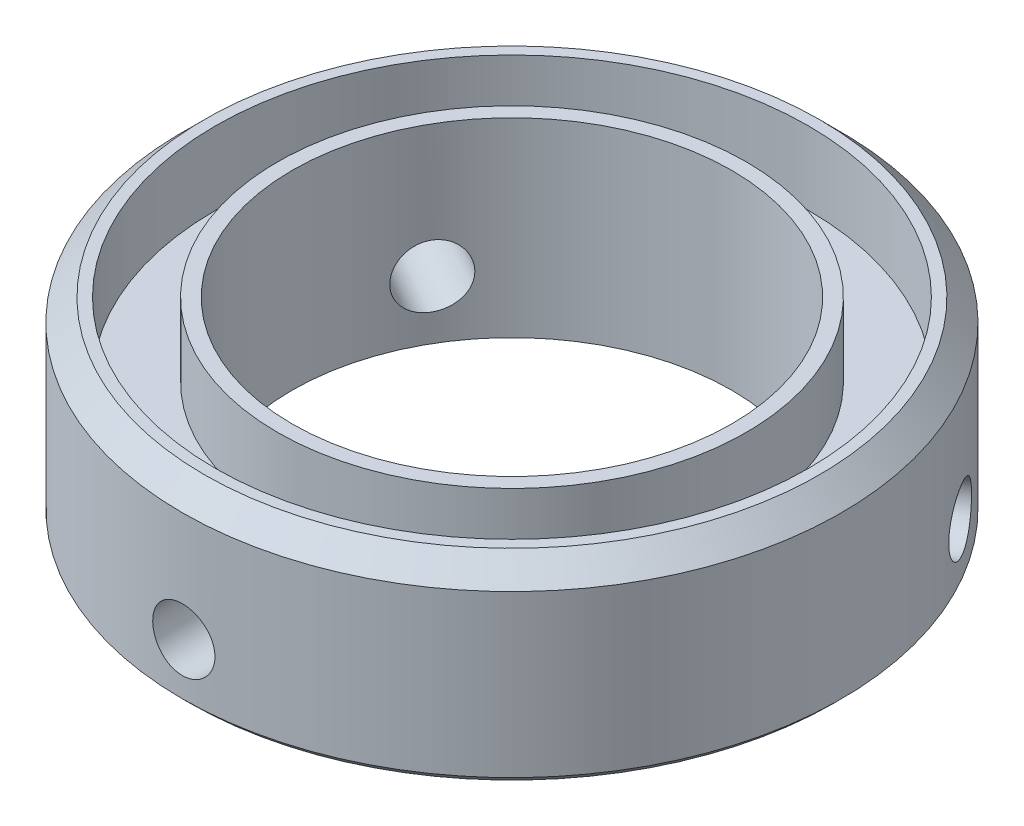
SolidWorks part; units mm, degrees
material "AISI 304"
ref_plane "Piano frontale" through (0, 0, 0) normal (0, 0, 1) x (1, 0, 0)
ref_plane "Piano superiore" through (0, 0, 0) normal (0, 1, 0) x (1, 0, 0)
ref_plane "Piano destro" through (0, 0, 0) normal (1, 0, 0) x (0, 0, -1)
sketch "Schizzo1" plane through (0, 0, 0) normal (0, 1, 0) x (1, 0, 0)
  circle A0 centre (0, 0) radius 30
  circle A1 centre (0, 0) radius 45
  dimension "D1" = 60
  dimension "D2" = 90
extrude "Estrusione1" add sketch "Schizzo1" along normal blind 26
sketch "Schizzo2" plane through (0, 26, 0) normal (0, 1, 0) x (1, 0, 0)
  circle A0 centre (0, 0) radius 32
  circle A1 centre (0, 0) radius 40.5
  dimension "D1" = 64
  dimension "D2" = 81
extrude "Estrusione2" cut sketch "Schizzo2" against normal blind 10
ref_plane "Piano1" through (0, 0, 45) normal (0, 0, 1) x (1, 0, 0)
hole_wizard "Foro filettato M10-1" positions "Schizzo4" profile "Schizzo3" tap size "M10" standard "ISO"
sketch "Schizzo4" plane through (0, 0, 45) normal (0, 0, 1) x (1, 0, 0)
  line L0 (0, 0) -> (0, 20.8256) construction
  line L1 (-45, 0) -> (45, 0) construction
  line L2 (32, 16) -> (-32, 16) construction
  point P0 (0, 8)
  dimension "D1" = 8
sketch "Schizzo3" plane through (0, 8, 45) normal (1, 0, 0) x (0, -1, 0)
  line L0 (0, 0) -> (0, 50.0537)
  line L1 (0, 50.0537) -> (4.25, 47.5)
  line L2 (4.25, 47.5) -> (4.25, 0)
  line L5 (4.25, 0) -> (0, 0)
  line L10 (0, 50.0537) -> (-4.25, 47.5) construction
  line L11 (0, -6.35) -> (0, 107.95) construction
  dimension "Tap Drill Dia." = 8.5
  dimension "Tap Drill Depth" = 47.5
  dimension "Drill Angle" = 118
cosmetic thread "Filettatura del foro1" parameters "D1"=20, "D2"=10
pattern_circular "RipetizioneCircolare1" count 3 over 360 about axis through (0, 26, 0) along (0, -1, 0) of "Foro filettato M10-1"
chamfer "Smusso1" distance 3 angle 45 1 edges at (0, 26, 45)
chamfer "Smusso2" distance 1 angle 45 1 edges at (0, 0, 45)
